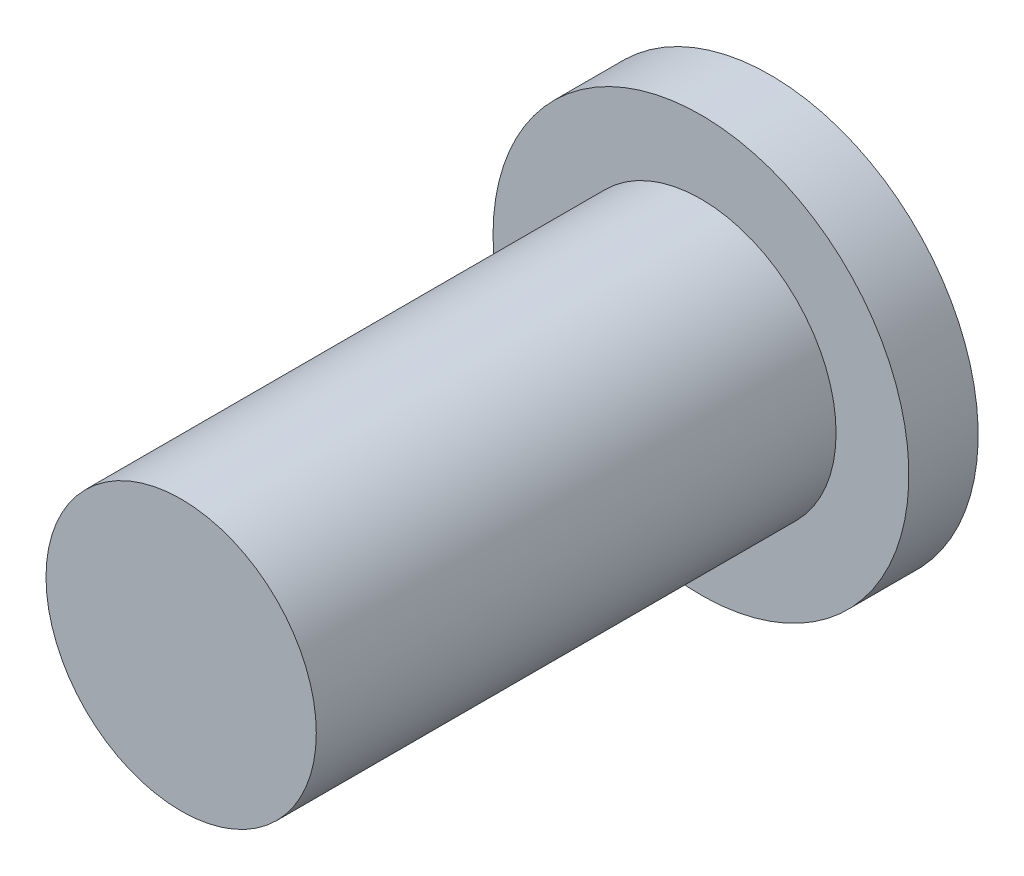
SolidWorks part; units mm, degrees
ref_plane "前视基准面" through (0, 0, 0) normal (0, 0, 1) x (1, 0, 0)
ref_plane "上视基准面" through (0, 0, 0) normal (0, 1, 0) x (1, 0, 0)
ref_plane "右视基准面" through (0, 0, 0) normal (1, 0, 0) x (0, 0, -1)
sketch "草图1" plane through (0, 0, 0) normal (0, 0, 1) x (1, 0, 0)
  circle A0 centre (0, 0) radius 3.9
extrude "凸台-拉伸1" add sketch "草图1" along normal blind 15
sketch "草图2" plane through (0, 0, 0) normal (0, 0, -1) x (-1, 0, 0)
  circle A0 centre (0, 0) radius 6
extrude "凸台-拉伸2" add sketch "草图2" along normal blind 2
